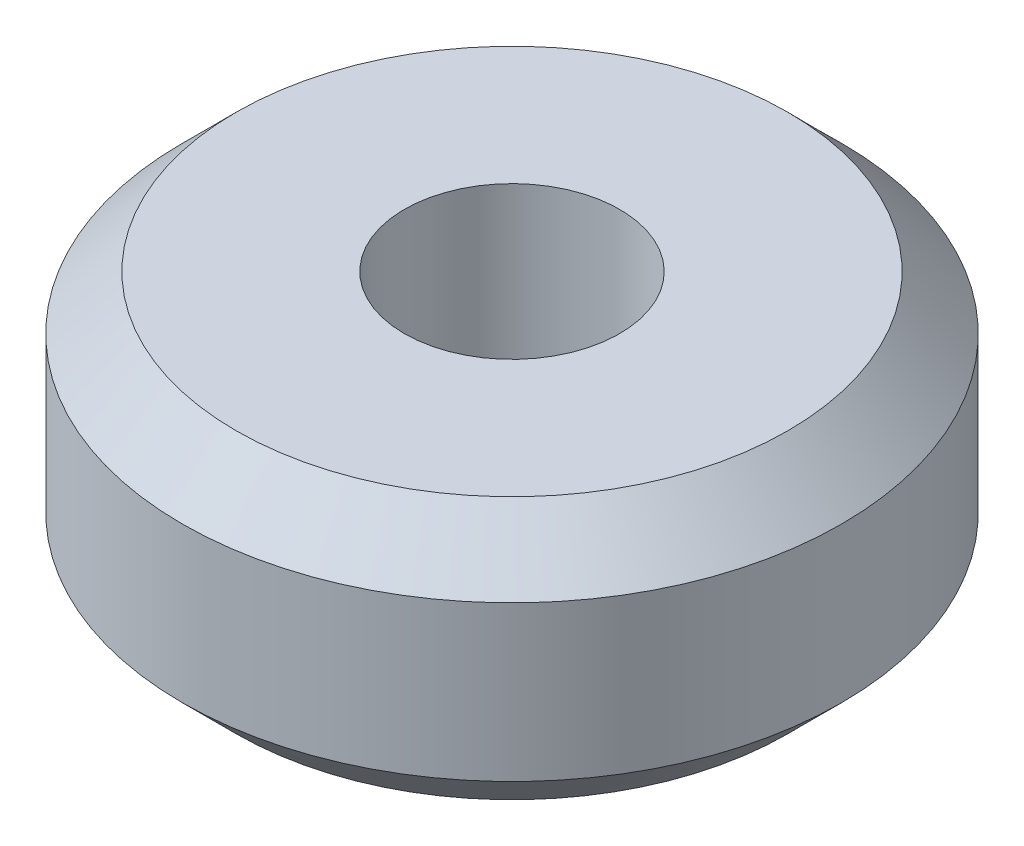
SolidWorks part; units mm, degrees
ref_plane "Front Plane" through (0, 0, 0) normal (0, 0, 1) x (1, 0, 0)
ref_plane "Top Plane" through (0, 0, 0) normal (0, 1, 0) x (1, 0, 0)
ref_plane "Right Plane" through (0, 0, 0) normal (1, 0, 0) x (0, 0, -1)
sketch "Sketch1" plane through (0, 0, 0) normal (0, 1, 0) x (1, 0, 0)
  circle A0 centre (0, 0) radius 1.6
  circle A1 centre (0, 0) radius 4.9
  dimension "D1" = 3.2
  dimension "D2" = 9.8
extrude "Boss-Extrude1" add sketch "Sketch1" along normal blind 3.9
chamfer "Chamfer1" distance 0.8 angle 45 2 edges at (0, 0, 4.9) (0, 3.9, 4.9)
equation "\"í.8\"=1"
